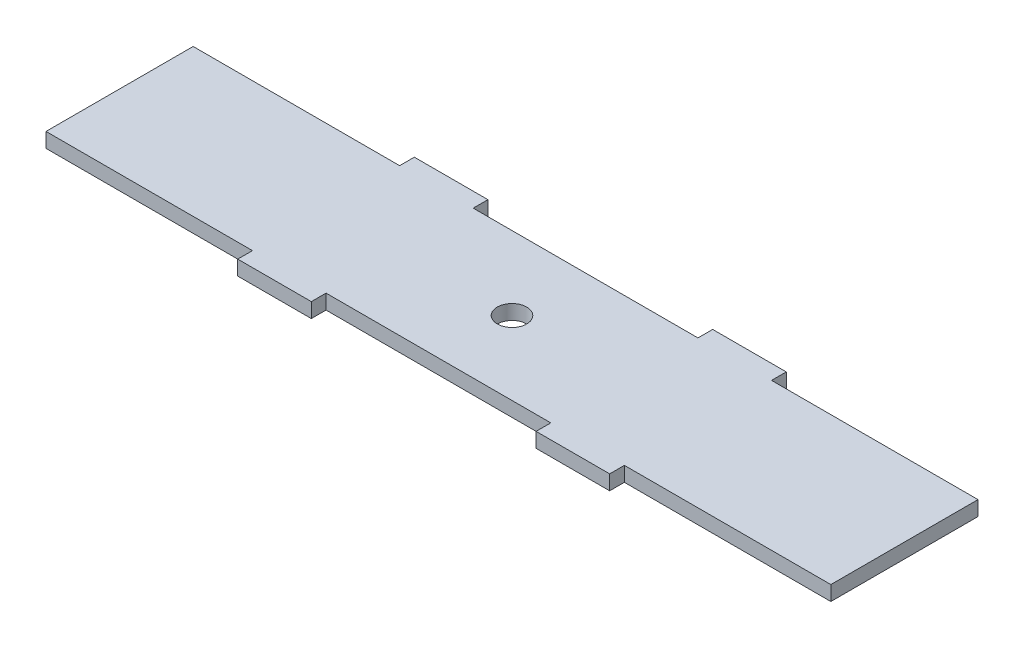
SolidWorks part; units mm, degrees
ref_plane "Front Plane" through (0, 0, 0) normal (0, 0, 1) x (1, 0, 0)
ref_plane "Top Plane" through (0, 0, 0) normal (0, 1, 0) x (1, 0, 0)
ref_plane "Right Plane" through (0, 0, 0) normal (1, 0, 0) x (0, 0, -1)
sketch "Sketch2" plane through (0, 0, 0) normal (0, 1, 0) x (1, 0, 0)
  line L0 (0, -15) -> (160, -15) construction
  line L1 (0, 0) -> (42.09, 0)
  line L2 (0, 0) -> (0, -30)
  line L3 (0, -30) -> (42.09, -30)
  line L4 (160, 0) -> (160, -30)
  line L5 (80, 0) -> (80, -85.6563) construction
  line L6 (117.91, -33) -> (102.91, -33)
  line L8 (42.09, -30) -> (42.09, -33)
  line L9 (42.09, -33) -> (57.09, -33)
  line L10 (57.09, -30) -> (57.09, -33)
  line L11 (102.91, -30) -> (102.91, -33)
  line L13 (117.91, -30) -> (117.91, -33)
  line L14 (117.91, 0) -> (117.91, 3)
  line L16 (102.91, 0) -> (102.91, 3)
  line L17 (117.91, 3) -> (102.91, 3)
  line L18 (42.09, 3) -> (57.09, 3)
  line L19 (57.09, 0) -> (57.09, 3)
  line L21 (42.09, 0) -> (42.09, 3)
  line L22 (57.09, 0) -> (102.91, 0)
  line L23 (57.09, -30) -> (102.91, -30)
  line L24 (117.91, 0) -> (160, 0)
  line L25 (117.91, -30) -> (160, -30)
  circle A0 centre (80, -15) radius 3
  dimension "D6" = 6
  dimension "D1" = 160
  dimension "D2" = 30
  dimension "D3" = 15
  dimension "D4" = 3
  dimension "D5" = 42.09
extrude "Boss-Extrude1" add sketch "Sketch2" along normal blind 3
